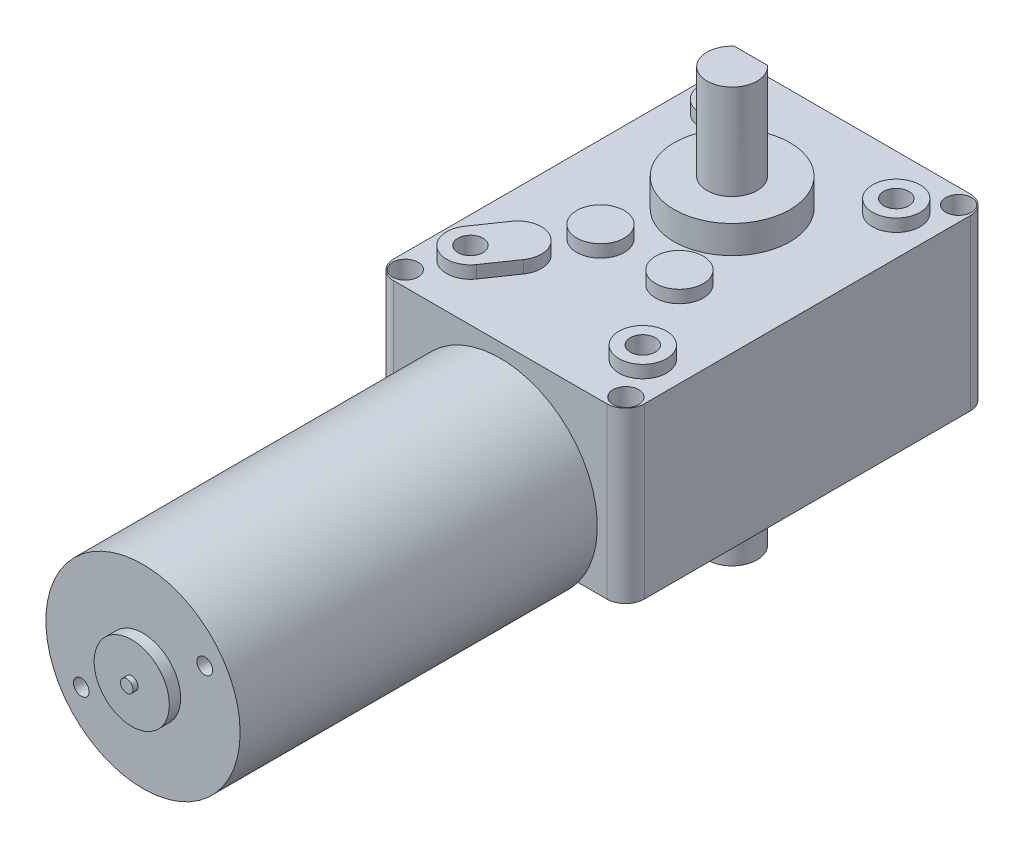
SolidWorks part; units mm, degrees
ref_plane "Front Plane" through (0, 0, 0) normal (0, 0, 1) x (1, 0, 0)
ref_plane "Top Plane" through (0, 0, 0) normal (0, 1, 0) x (1, 0, 0)
ref_plane "Right Plane" through (0, 0, 0) normal (1, 0, 0) x (0, 0, -1)
sketch "Sketch1" plane through (0, 0, 0) normal (0, 1, 0) x (1, 0, 0)
  line L1 (17.005, -29) -> (-17.005, -29)
  line L2 (20.005, -26) -> (20.005, 26)
  line L3 (17.005, 29) -> (-17.005, 29)
  line L4 (-20.005, -26) -> (-20.005, 26)
  line L5 (20.005, -29) -> (-20.005, 29) construction
  line L6 (20.005, 29) -> (-20.005, -29) construction
  arc A0 (-17.005, -29) -> (-20.005, -26) centre (-17.005, -26) cw
  arc A1 (17.005, -29) -> (20.005, -26) centre (17.005, -26) ccw
  arc A2 (20.005, 26) -> (17.005, 29) centre (17.005, 26) ccw
  arc A3 (-17.005, 29) -> (-20.005, 26) centre (-17.005, 26) ccw
  point P0 (0, 0)
  dimension "D1" = 40.01
  dimension "D2" = 58
  dimension "D3" = 3
extrude "Boss-Extrude2" add sketch "Sketch1" along normal blind 27
ref_plane "Plane1" through (0, 13.5, 0) normal (0, 1, 0) x (1, 0, 0)
sketch "Sketch5" plane through (0, 27, 0) normal (0, 1, 0) x (1, 0, 0)
  line L0 (-13.75, -20) -> (-10.6907, -15.5502) construction
  line L1 (-16.8814, -17.8472) -> (-13.8221, -13.3974)
  line L2 (-10.6186, -22.1528) -> (-7.5594, -17.703)
  line L3 (-17.005, -29) -> (17.005, -29) construction
  line L4 (0, -29) -> (0, 29) construction
  line L5 (17.005, 29) -> (-17.005, 29) construction
  circle A0 centre (-13.75, 20.45) radius 3.8
  circle A1 centre (13.75, 20.45) radius 3.8
  circle A2 centre (13.75, -20) radius 3.8
  arc A3 (-16.8814, -17.8472) -> (-10.6186, -22.1528) centre (-13.75, -20) ccw
  arc A4 (-7.5594, -17.703) -> (-13.8221, -13.3974) centre (-10.6907, -15.5502) ccw
  circle A5 centre (-6.3, -6.7) radius 3.8
  circle A6 centre (6.3, -6.7) radius 3.8
  point P8 (-12.2204, -17.7751)
  dimension "D2" = 5.4
  dimension "D5" = 12.6
  dimension "D7" = 22.3
  dimension "D6" = 7.6
  dimension "D8" = 7.6
  dimension "D1" = 7.6
  dimension "D3" = 40.45
  dimension "D4" = 9
  dimension "D9" = 27.5
extrude "Boss-Extrude3" add sketch "Sketch5" along normal blind 2
sketch "Sketch6" plane through (0, 29, 0) normal (0, 1, 0) x (1, 0, 0)
  circle A0 centre (13.75, -20) radius 2
  circle A1 centre (13.75, 20.45) radius 2
  circle A2 centre (-13.75, 20.45) radius 2
  circle A3 centre (-13.75, -20) radius 2
  arc A4 (-16.8814, -17.8472) -> (-10.6186, -22.1528) centre (-13.75, -20) ccw construction
  point P11 (-12.4064, -16.6635)
  point P12 (-13.75, -20)
  point P13 (-10.8658, -14.9607)
  point P17 (0, 0)
  dimension "D1" = 4
extrude "Cut-Extrude3" cut sketch "Sketch6" against normal blind 4
sketch "Sketch7" plane through (0, 27, 0) normal (0, 1, 0) x (1, 0, 0)
  line L0 (-17.005, -29) -> (17.005, -29) construction
  circle A0 centre (0, 8) radius 9.25
  point P5 (0, 0)
  dimension "D1" = 18.5
  dimension "D2" = 37
extrude "Boss-Extrude4" add sketch "Sketch7" along normal blind 4.45
sketch "Sketch8" plane through (0, 31.45, 0) normal (0, 1, 0) x (1, 0, 0)
  circle A0 centre (0, 8) radius 4
  dimension "D1" = 8
extrude "Boss-Extrude5" add sketch "Sketch8" along normal blind 15.14
sketch "Sketch9" plane through (0, 46.59, 0) normal (0, 1, 0) x (1, 0, 0)
  line L0 (-2.6458, 11) -> (2.6458, 11)
  circle A0 centre (0, 8) radius 4 construction
  arc A1 (2.6458, 11) -> (-2.6458, 11) centre (0, 8) ccw
  dimension "D1" = 3
extrude "Cut-Extrude4" cut sketch "Sketch9" against normal blind 13
mirror "Mirror1" about plane through (0, 13.5, 0) normal (0, 1, 0) of "Cut-Extrude4", "Boss-Extrude5", "Boss-Extrude4", "Cut-Extrude3", "Boss-Extrude3"
sketch "Sketch11" plane through (0, 0, 29) normal (0, 0, 1) x (1, 0, 0)
  line L4 (-17.005, 0) -> (17.005, 0) construction
  circle A0 centre (0, 9.3) radius 15.5
  point P4 (0, 12.6004)
  point P7 (0, 0)
  dimension "D1" = 31
  dimension "D2" = 9.3
extrude "Boss-Extrude6" add sketch "Sketch11" along normal blind 57
sketch "Sketch12" plane through (0, 0, 86) normal (0, 0, 1) x (1, 0, 0)
  circle A0 centre (0, 9.3) radius 6
  dimension "D1" = 12
extrude "Boss-Extrude7" add sketch "Sketch12" along normal blind 1.8
sketch "Sketch13" plane through (0, 0, 87.8) normal (0, 0, 1) x (1, 0, 0)
  circle A0 centre (0, 9.3) radius 1
  dimension "D1" = 2
extrude "Boss-Extrude8" add sketch "Sketch13" along normal blind 0.8
sketch "Sketch14" plane through (0, 0, 86) normal (0, 0, 1) x (1, 0, 0)
  line L0 (0, 9.3) -> (9.8544, 15.6995) construction
  line L1 (0, 9.3) -> (0, 24.8) construction
  circle A0 centre (0, 9.3) radius 11.75 construction
  circle A1 centre (9.8544, 15.6995) radius 1.25
  circle A3 centre (-9.8544, 2.9005) radius 1.25
  circle A4 centre (0, 9.3) radius 15.5 construction
  point P11 (0, 9.3)
  dimension "D1" = 23.5
  dimension "D2" = 57
  dimension "D3" = 2
  dimension "D4" = 2.5
extrude "Cut-Extrude6" cut sketch "Sketch14" against normal blind 4
sketch "Sketch10" plane through (0, 27, 0) normal (0, 1, 0) x (1, 0, 0)
  line L0 (0, 29) -> (0, -29) construction
  line L1 (17.005, 29) -> (-17.005, 29) construction
  line L2 (-17.005, -29) -> (17.005, -29) construction
  line L3 (-20.005, 0) -> (20.005, 0) construction
  line L4 (-20.005, 26) -> (-20.005, -26) construction
  line L5 (20.005, -26) -> (20.005, 26) construction
  circle A0 centre (-17.6, 26.55) radius 2.05
  circle A1 centre (17.6, 26.55) radius 2.05
  circle A2 centre (17.6, -26.55) radius 2.05
  circle A3 centre (-17.6, -26.55) radius 2.05
  point P14 (0, 0)
  dimension "D3" = 4.1
  dimension "D1" = 35.2
  dimension "D2" = 2.45
extrude "Cut-Extrude5" cut sketch "Sketch10" against normal blind 4
